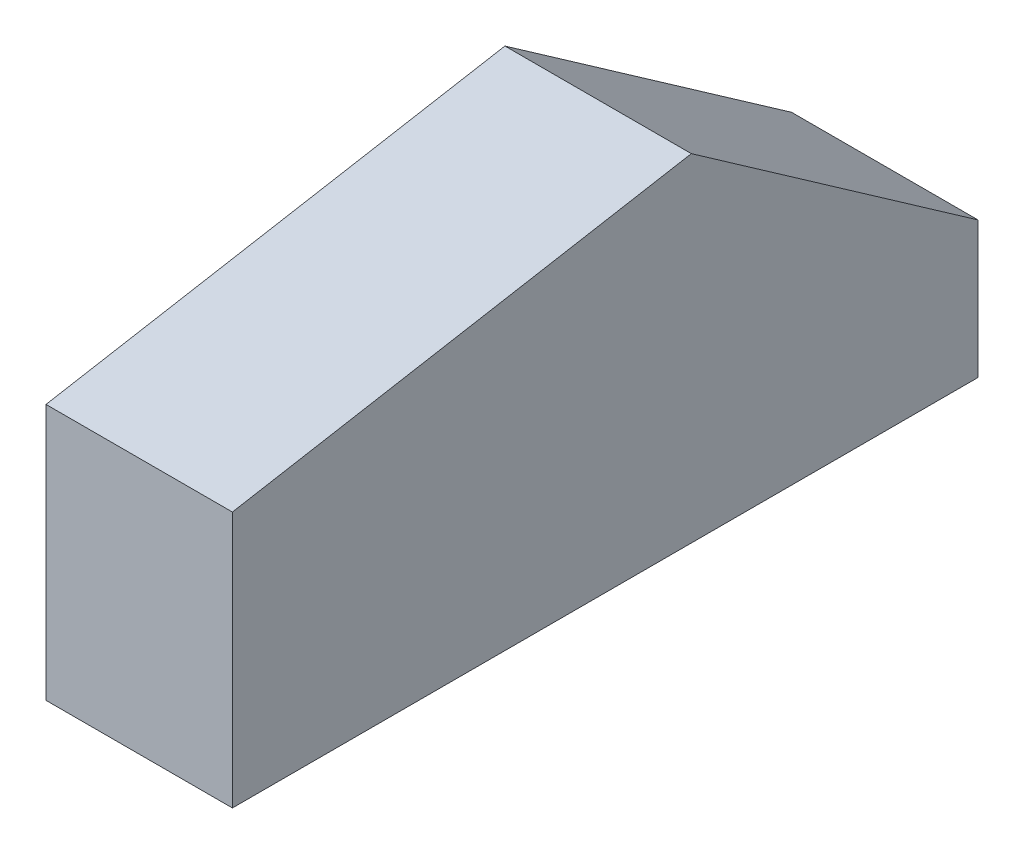
SolidWorks part; units mm, degrees
ref_plane "Front Plane" through (0, 0, 0) normal (0, 0, 1) x (1, 0, 0)
ref_plane "Top Plane" through (0, 0, 0) normal (0, 1, 0) x (1, 0, 0)
ref_plane "Right Plane" through (0, 0, 0) normal (1, 0, 0) x (0, 0, -1)
sketch "Sketch2" plane through (0, 0, 0) normal (1, 0, 0) x (0, 0, -1)
  line L0 (0, 0) -> (4, 0)
  line L1 (0, 0) -> (0, 1.375)
  line L2 (0, 1.375) -> (2.462, 1.8091)
  line L3 (4, 0) -> (4, 0.7322)
  line L4 (2.462, 1.8091) -> (4, 0.7322)
  dimension "D1" = 2.5
  dimension "D2" = 1.375
  dimension "D3" = 4
  dimension "D4" = 135
  dimension "D5" = 100
  dimension "D6" = 90
  dimension "D7" = 90
  dimension "D8" = 125
extrude "Boss-Extrude1" add sketch "Sketch2" along normal blind 1 contours L3 L4 L2 L1 L0
